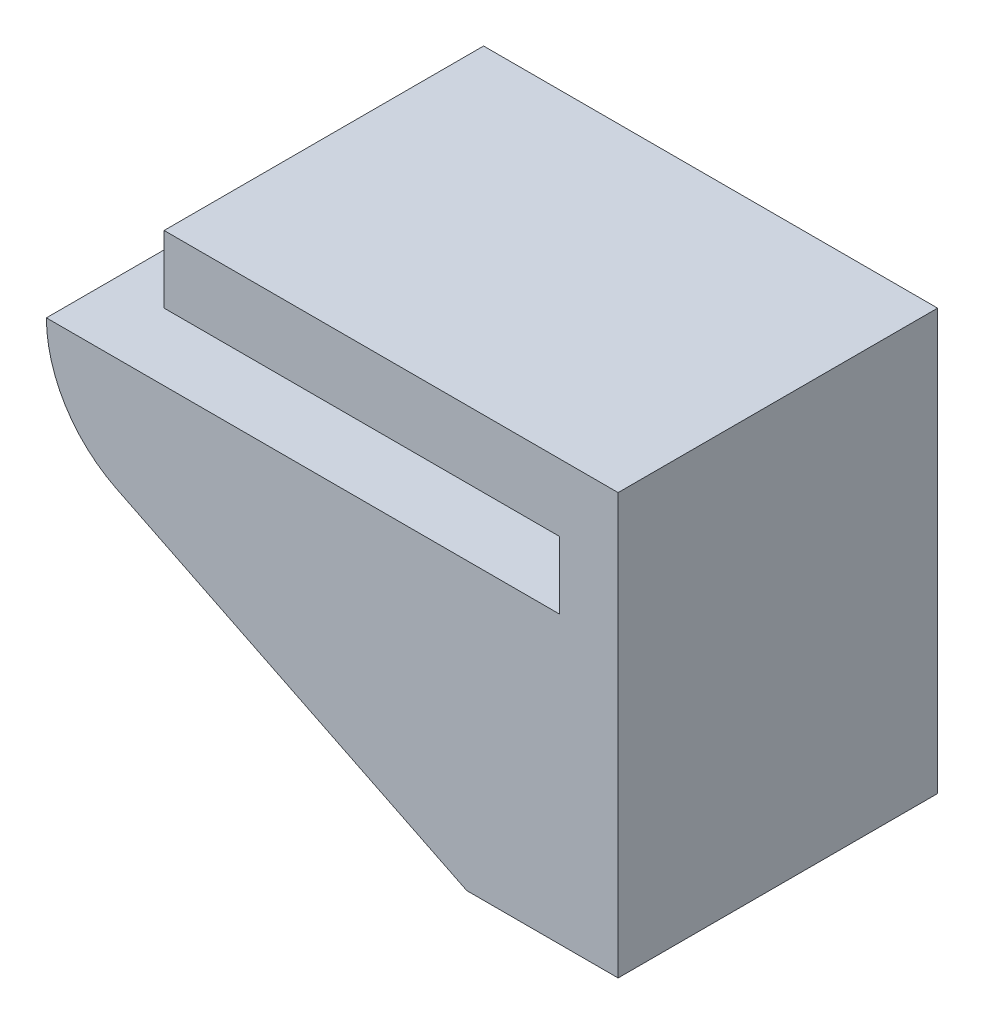
SolidWorks part; units mm, degrees
ref_plane "Front Plane" through (0, 0, 0) normal (0, 0, 1) x (1, 0, 0)
ref_plane "Top Plane" through (0, 0, 0) normal (0, 1, 0) x (1, 0, 0)
ref_plane "Right Plane" through (0, 0, 0) normal (1, 0, 0) x (0, 0, -1)
sketch "Sketch1" plane through (0, 0, 0) normal (0, 0, 1) x (1, 0, 0)
  line L0 (0, 8) -> (0, -17)
  line L1 (-9, -17) -> (-29.8191, -6.7256)
  line L2 (-34, 0) -> (-3.5, 0)
  line L3 (-3.5, 0) -> (-3.5, 4)
  line L4 (-3.5, 4) -> (-27, 4)
  line L5 (-27, 4) -> (-27, 8)
  line L6 (-27, 8) -> (0, 8)
  line L7 (-9, -17) -> (0, -17)
  arc A0 (-34, 0) -> (-29.8191, -6.7256) centre (-26.5, 0) ccw
  dimension "D8" = 15
  dimension "D1" = 4
  dimension "D2" = 4
  dimension "D3" = 27
  dimension "D4" = 34
  dimension "D5" = 3.5
  dimension "D6" = 9
  dimension "D7" = 25
extrude "Boss-Extrude1" add sketch "Sketch1" along normal blind 19
